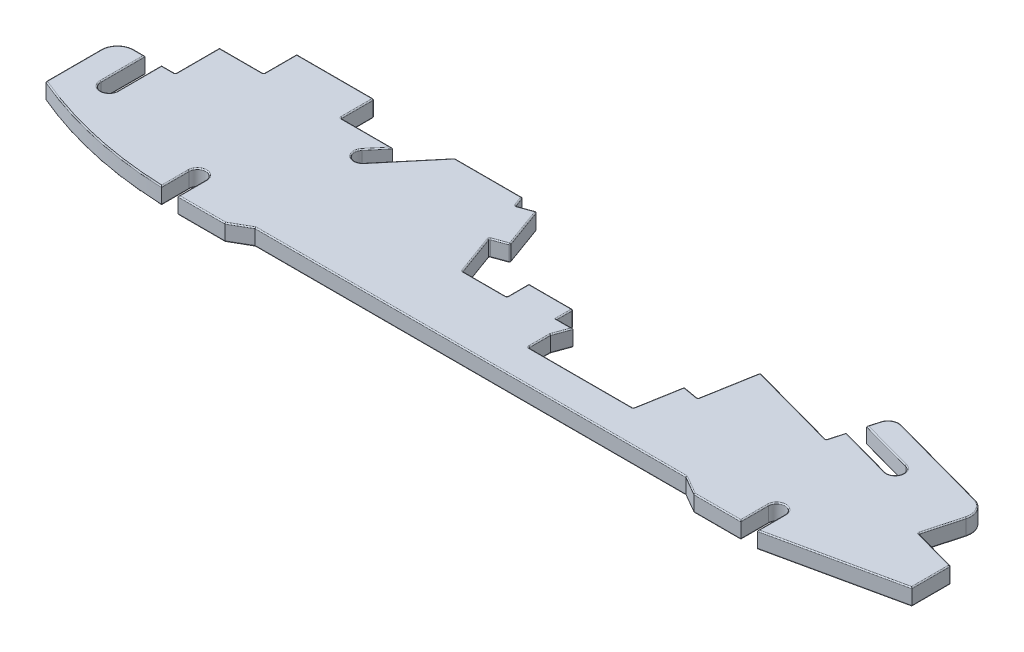
SolidWorks part; units mm, degrees
ref_plane "Front Plane" through (0, 0, 0) normal (0, 0, 1) x (1, 0, 0)
ref_plane "Top Plane" through (0, 0, 0) normal (0, 1, 0) x (1, 0, 0)
ref_plane "Right Plane" through (0, 0, 0) normal (1, 0, 0) x (0, 0, -1)
sketch "Sketch1" plane through (0, 0, 0) normal (0, 1, 0) x (1, 0, 0)
  line L0 (-1.5, 0) -> (-1.5, -5)
  line L1 (1.5, 0) -> (1.5, -5)
  line L2 (-103.5, -5) -> (-95, -5)
  line L3 (24.5, 0) -> (24.5, 7)
  line L4 (-103.5, -5) -> (-103.5, 0)
  line L5 (-106.5, 0) -> (-106.5, -5)
  line L8 (-133.5, 11) -> (-133.5, 1)
  line L9 (1.5, -5) -> (24.5, 0)
  line L10 (-91.5359, -3) -> (-13.4641, -3)
  line L11 (-95, -5) -> (-91.5359, -3)
  line L12 (-10, -5) -> (-13.4641, -3)
  line L13 (-10, -5) -> (-1.5, -5)
  line L14 (-105, 0) -> (0, 0) construction
  line L15 (-52.5, 0) -> (-52.5, -7.0386) construction
  line L16 (-48, 3) -> (-29, 3)
  line L18 (-48, 3) -> (-48, 7)
  line L19 (-48, 7) -> (-46.9081, 10)
  line L20 (-46.9081, 10) -> (-49.9081, 10)
  line L21 (-49.9081, 10) -> (-49.9081, 13)
  line L22 (-49.9081, 13) -> (-57.9081, 13)
  line L23 (-57.9081, 13) -> (-57.9081, 9)
  line L24 (-57.9081, 9) -> (-65.9081, 9)
  line L25 (-65.9081, 9) -> (-68.6443, 16.5175)
  line L26 (-84.3291, 26) -> (-72.0956, 26)
  line L27 (-68.6443, 16.5175) -> (-65.8252, 17.5436)
  line L28 (-65.8252, 17.5436) -> (-68.5613, 25.0611)
  line L29 (-68.5613, 25.0611) -> (-71.3804, 24.0351)
  line L30 (-71.3804, 24.0351) -> (-72.0956, 26)
  line L31 (-115, 28) -> (-101, 28)
  line L32 (-101, 28) -> (-101, 22)
  line L33 (-101, 22) -> (-91.6017, 22)
  line L34 (-91.6017, 22) -> (-94.1491, 18.9642)
  line L35 (-91.8509, 17.0358) -> (-84.3291, 26)
  line L36 (-115, 28) -> (-115, 22)
  line L37 (-115, 22) -> (-123, 22)
  line L38 (-123, 22) -> (-123, 14)
  line L39 (-123, 14) -> (-125.5, 14)
  line L41 (-29, 3) -> (-27.6108, 10.8785)
  line L42 (-27.6108, 10.8785) -> (-24.6564, 10.3575)
  line L43 (-24.6564, 10.3575) -> (-22.9562, 20)
  line L44 (24.5, 7) -> (16.587, 9.1677)
  line L45 (-6.5602, 15.5085) -> (-5.7676, 18.4019)
  line L46 (-5.7676, 18.4019) -> (3.8771, 15.7599)
  line L47 (4.6697, 18.6533) -> (-4.975, 21.2953)
  line L48 (-4.975, 21.2953) -> (-4.4466, 23.2243)
  line L49 (-1.9893, 24.6248) -> (16.3356, 19.6049)
  line L50 (18.4364, 15.9189) -> (16.587, 9.1677)
  line L51 (-6.5602, 15.5085) -> (-22.9562, 20)
  line L52 (-128.5, 6) -> (-128.5, 14)
  line L53 (-125.5, 6) -> (-125.5, 14)
  line L54 (-128.5, 14) -> (-130.5, 14)
  arc A0 (1.5, 0) -> (-1.5, 0) centre (0, 0) ccw
  arc A1 (-103.5, 0) -> (-106.5, 0) centre (-105, 0) ccw
  arc A2 (-133.5, 11) -> (-130.5, 14) centre (-130.5, 11) cw
  arc A4 (-133.5, 1) -> (-106.5, -5) centre (-104.0092, 69.9586) ccw
  arc A5 (-94.1491, 18.9642) -> (-91.8509, 17.0358) centre (-93, 18) ccw
  arc A6 (3.8771, 15.7599) -> (4.6697, 18.6533) centre (4.2734, 17.2066) ccw
  arc A7 (16.3356, 19.6049) -> (18.4364, 15.9189) centre (15.543, 16.7115) cw
  arc A8 (-4.4466, 23.2243) -> (-1.9893, 24.6248) centre (-2.5177, 22.6959) cw
  arc A9 (-128.5, 6) -> (-125.5, 6) centre (-127, 6) ccw
  point P68 (19.229, 18.8123)
  point P71 (-3.9182, 25.1532)
  dimension "D1" = 3
  dimension "D3" = 3
  dimension "D10" = 75
  dimension "D36" = 14
  dimension "D42" = 1.5
  dimension "D49" = 23
  dimension "D52" = 1.5
  dimension "D56" = 3
  dimension "D57" = 2
  dimension "D58" = 3
  dimension "D47" = 3
  dimension "D2" = 24.5
  dimension "D4" = 105
  dimension "D7" = 28.5
  dimension "D8" = 10.5
  dimension "D9" = 6
  dimension "D11" = 5
  dimension "D12" = 5
  dimension "D13" = 12
  dimension "D14" = 2
  dimension "D15" = 30
  dimension "D16" = 30
  dimension "D17" = 85
  dimension "D18" = 42.5
  dimension "D19" = 6
  dimension "D20" = 4
  dimension "D21" = 48
  dimension "D22" = 29
  dimension "D23" = 20
  dimension "D24" = 13
  dimension "D25" = 8
  dimension "D26" = 8
  dimension "D27" = 12
  dimension "D28" = 3
  dimension "D29" = 3
  dimension "D30" = 29
  dimension "D31" = 70
  dimension "D32" = 8
  dimension "D33" = 8
  dimension "D34" = 3
  dimension "D35" = 33
  dimension "D37" = 6
  dimension "D38" = 8
  dimension "D39" = 8
  dimension "D40" = 8
  dimension "D41" = 12
  dimension "D43" = 40
  dimension "D44" = 23
  dimension "D45" = 80
  dimension "D46" = 3
  dimension "D50" = 17
  dimension "D51" = 3
  dimension "D53" = 10
  dimension "D54" = 4
  dimension "D55" = 24
  dimension "D59" = 6.5
  dimension "D60" = 8
extrude "Boss-Extrude1" add sketch "Sketch1" along normal blind 3
fillet "Fillet1" radius 0.2 118 edges at (-29, 1.5, -3) (-49.9081, 1.5, -13) (-57.9081, 1.5, -13) (-65.8252, 1.5, -17.5436) (-68.5613, 1.5, -25.0611) (13, 0, 2.5) (24.5, 0, -3.5) (20.5435, 0, -8.0838) (17.5117, 0, -12.5433) (18.1494, 0, -18.197) (7.1732, 0, -22.1149) (-3.508, 0, -24.4335) (-4.7108, 0, -22.2598) (-0.1527, 0, -19.9743) (5.7201, 0, -16.8103) (-0.9453, 0, -17.0809) (-6.1639, 0, -16.9552) (-14.7582, 0, -17.7543) (-23.8063, 0, -15.1788) (-47.454, 0, -8.5) (-48.4081, 0, -10) (-49.9081, 0, -11.5) (-53.9081, 0, -13) (-57.9081, 0, -11) (-61.9081, 0, -9) (-67.2762, 0, -12.7588) (-67.2347, 0, -17.0306) (-67.1933, 0, -21.3024) (-69.9709, 0, -24.5481) (-71.738, 0, -25.0175) (-78.2123, 0, -26) (-88.09, 0, -21.5179) (-93.9642, 0, -16.8509) (-92.8754, 0, -20.4821) (-96.3009, 0, -22) (-101, 0, -25) (-108, 0, -28) (-115, 0, -25) (-123, 0, -18) (-125.5, 0, -10) (-128.5, 0, -10) (-129.5, 0, -14) (-133.5, 0, -6) (-106.5, 0, 2.5) (-105, 0, -1.5) (-103.5, 0, 2.5) (-99.25, 0, 5) (-93.2679, 0, 4) (-52.5, 0, 3) (-11.7321, 0, 4) (-5.75, 0, 5) (-1.5, 0, 2.5) (0, 0, -1.5) (-1.5, 3, 2.5) (-5.75, 3, 5) (-11.7321, 3, 4) (-93.2679, 3, 4) (-99.25, 3, 5) (-103.5, 3, 2.5) (-105, 3, -1.5) (-106.5, 3, 2.5) (-120.279, 3, 3.2554) (-133.5, 3, -6) (-129.5, 3, -14) (-127, 3, -4.5) (-125.5, 3, -10) (-123, 3, -18) (-119, 3, -22) (-115, 3, -25) (-108, 3, -28) (-101, 3, -25) (-96.3009, 3, -22) (-92.8754, 3, -20.4821) (-93.9642, 3, -16.8509) (-88.09, 3, -21.5179) (-78.2123, 3, -26) (-71.738, 3, -25.0175) (-69.9709, 3, -24.5481) (-67.1933, 3, -21.3024) (-67.2347, 3, -17.0306) (-67.2762, 3, -12.7588) (-61.9081, 3, -9) (-57.9081, 3, -11) (-53.9081, 3, -13) (-49.9081, 3, -11.5) (-48.4081, 3, -10) (-47.454, 3, -8.5) (-23.8063, 3, -15.1788) (-14.7582, 3, -17.7543) (-6.1639, 3, -16.9552) (-0.9453, 3, -17.0809) (5.7201, 3, -16.8103) (-0.1527, 3, -19.9743) (-4.7108, 3, -22.2598) (-3.508, 3, -24.4335) (7.1732, 3, -22.1149) (18.1494, 3, -18.197) (17.5117, 3, -12.5433) (20.5435, 3, -8.0838) (24.5, 3, -3.5) (1.5, 3, 2.5) (0, 3, -1.5) (24.5, 1.5, -7) (16.587, 1.5, -9.1677) (-6.5602, 1.5, -15.5085) (-22.9562, 1.5, -20) (-24.6564, 1.5, -10.3575) (-57.9081, 1.5, -9) (-65.9081, 1.5, -9) (-68.6443, 1.5, -16.5175) (-71.3804, 1.5, -24.0351) (-72.0956, 1.5, -26) (-115, 1.5, -22) (-123, 1.5, -22) (-101, 1.5, -22) (-101, 1.5, -28) (-132.6213, 0, -13.1213) (-132.6213, 3, -13.1213)
